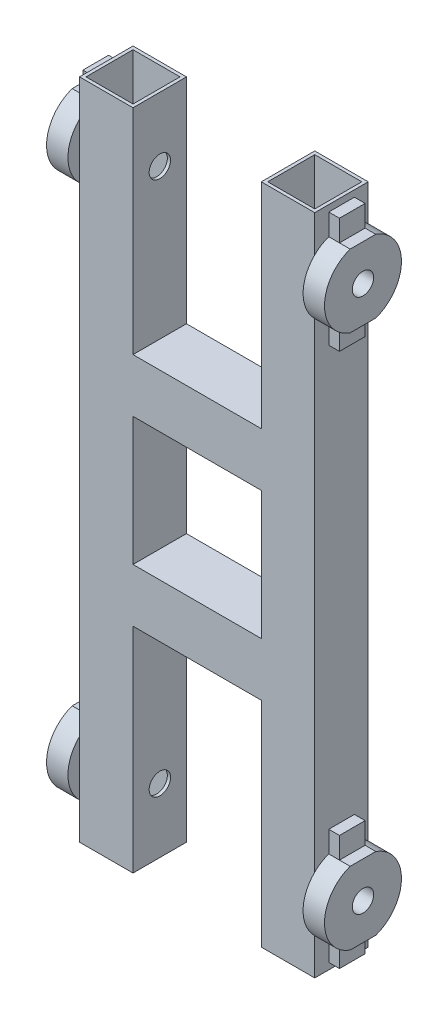
SolidWorks part; units mm, degrees
ref_plane "Front Plane" through (0, 0, 0) normal (0, 0, 1) x (1, 0, 0)
ref_plane "Top Plane" through (0, 0, 0) normal (0, 1, 0) x (1, 0, 0)
ref_plane "Right Plane" through (0, 0, 0) normal (1, 0, 0) x (0, 0, -1)
sketch "Sketch1" plane through (0, 0, 0) normal (0, 1, 0) x (1, 0, 0)
  line L0 (0, 63.6278) -> (0, -69.3975) construction
  line L1 (-105.4586, 0) -> (105.4586, 0) construction
  line L2 (19.5, 10.942) -> (19.5, -11.058)
  line L3 (18, 12.442) -> (43, 12.442)
  line L4 (18, 12.442) -> (18, -12.558)
  line L5 (18, -12.558) -> (43, -12.558)
  line L6 (43, 12.442) -> (43, -12.558)
  line L7 (19.5, -11.058) -> (41.5, -11.058)
  line L8 (41.5, 10.942) -> (41.5, -11.058)
  line L13 (19.5, 10.942) -> (41.5, 10.942)
  point P5 (30.442, 0)
  point P10 (30.5, -0.058)
  dimension "D1" = 25
  dimension "D2" = 25
  dimension "D3" = 18
  dimension "D4" = 1.5
extrude "Boss-Extrude1" add sketch "Sketch1" along normal blind 310
sketch "Sketch2" plane through (18, 0, 0) normal (-1, 0, 0) x (0, 0, 1)
  line L5 (12.558, 310) -> (12.558, 0) construction
  line L6 (-12.442, 210) -> (12.558, 210)
  line L7 (-12.442, 210) -> (-12.442, 185)
  line L8 (-12.442, 185) -> (12.558, 185)
  line L9 (12.558, 210) -> (12.558, 185)
  line L10 (-12.442, 210) -> (12.558, 185) construction
  line L11 (-12.442, 185) -> (12.558, 210) construction
  line L12 (-12.442, 310) -> (12.558, 310) construction
  line L13 (-10.942, 208.5) -> (-10.942, 186.5)
  line L14 (-12.442, 125) -> (12.558, 125)
  line L15 (-12.442, 125) -> (-12.442, 100)
  line L16 (-12.442, 100) -> (12.558, 100)
  line L17 (12.558, 125) -> (12.558, 100)
  line L18 (-12.442, 125) -> (12.558, 100) construction
  line L19 (-12.442, 100) -> (12.558, 125) construction
  line L20 (-10.942, 186.5) -> (11.058, 186.5)
  line L21 (11.058, 208.5) -> (11.058, 186.5)
  line L22 (-10.942, 208.5) -> (11.058, 208.5)
  line L23 (-10.942, 123.5) -> (-10.942, 101.5)
  line L24 (-10.942, 101.5) -> (11.058, 101.5)
  line L25 (11.058, 123.5) -> (11.058, 101.5)
  line L26 (-10.942, 123.5) -> (11.058, 123.5)
  point P0 (0.058, 197.5)
  point P9 (0.058, 112.5)
  dimension "D1" = 25
  dimension "D2" = 25
  dimension "D3" = 100
  dimension "D4" = 25
  dimension "D5" = 25
  dimension "D8" = 60
  dimension "D6" = 1.5
  dimension "D7" = 1.5
extrude "Boss-Extrude2" add sketch "Sketch2" along normal blind 30
sketch "Sketch8" plane through (18, 0, 0) normal (-1, 0, 0) x (0, 0, 1)
  line L0 (0, 340.3057) -> (0, -30.6599) construction
  line L1 (-12.442, 310) -> (12.558, 310) construction
  line L2 (-12.442, 0) -> (12.558, 0) construction
  circle A0 centre (0, 280) radius 5
  circle A1 centre (0, 30) radius 5
  point P11 (0, 0)
  dimension "D1" = 30
  dimension "D2" = 30
extrude "Cut-Extrude1" cut sketch "Sketch8" against normal blind 25
sketch "Sketch9" plane through (43, 0, 0) normal (1, 0, 0) x (0, 0, -1)
  line L0 (-6, 13.0294) -> (-6, 3.0294)
  line L24 (-6, 3.0294) -> (6, 3.0294)
  line L25 (6, 3.0294) -> (6, 13.0294)
  line L26 (-6, 46.9706) -> (-6, 56.9706)
  line L27 (-6, 56.9706) -> (6, 56.9706)
  line L28 (6, 56.9706) -> (6, 46.9706)
  circle A4 centre (0, 30) radius 5
  circle A5 centre (0, 30) radius 18
  arc A6 (-6, 46.9706) -> (6, 46.9706) centre (0, 30) cw
  arc A7 (-6, 13.0294) -> (6, 13.0294) centre (0, 30) ccw
  circle M17 centre (0, 30) radius 5
  line M21 (-12.558, 310) -> (-12.558, 0)
  dimension "D1" = 10
  dimension "D5" = 10
  dimension "D3" = 12
  dimension "D2" = 10
  dimension "D4" = 12
extrude "Boss-Extrude3" add sketch "Sketch9" along normal blind 10 contours A5 M17 | A5 L0 L24 L25 | A5 M21 | A5 L28 L27 L26 | A4
sketch "Sketch10" plane through (43, 0, 0) normal (1, 0, 0) x (0, 0, -1)
  line L0 (-6, 296.9706) -> (-6, 306.9706)
  line L1 (-6, 306.9706) -> (6, 306.9706)
  line L2 (6, 306.9706) -> (6, 296.9706)
  line L3 (-6, 263.0294) -> (-6, 253.0294)
  line L4 (-6, 253.0294) -> (6, 253.0294)
  line L5 (6, 253.0294) -> (6, 263.0294)
  circle A0 centre (0, 280) radius 18
  arc A1 (-6, 296.9706) -> (6, 296.9706) centre (0, 280) cw
  arc A2 (-6, 263.0294) -> (6, 263.0294) centre (0, 280) ccw
  circle A3 centre (0, 280) radius 5
  dimension "D1" = 12
  dimension "D2" = 10
  dimension "D3" = 10
  dimension "D4" = 10
  dimension "D5" = 12
  dimension "D6" = 10
extrude "Boss-Extrude4" add sketch "Sketch10" along normal blind 10
sketch "Sketch11" plane through (53, 0, 0) normal (1, 0, 0) x (0, 0, -1)
  line L0 (-6, 13.0294) -> (6, 13.0294)
  line L1 (6, 13.0294) -> (6, 3.0294)
  line L2 (-6, 3.0294) -> (6, 3.0294) construction
  line L3 (6, 3.0294) -> (6, 13.0294) construction
  line L4 (6, 3.0294) -> (-6, 3.0294)
  line L5 (-6, 3.0294) -> (-6, 13.0294)
  line L6 (-6, 46.9706) -> (6, 46.9706)
  line L7 (6, 46.9706) -> (6, 56.9706)
  line L8 (6, 56.9706) -> (-6, 56.9706)
  line L9 (-6, 56.9706) -> (-6, 46.9706)
  line L10 (-6, 263.0294) -> (-6, 253.0294)
  line L11 (-6, 253.0294) -> (6, 253.0294)
  line L12 (6, 253.0294) -> (6, 263.0294)
  line L13 (6, 263.0294) -> (-6, 263.0294)
  line L14 (-6, 296.9706) -> (-6, 306.9706)
  line L15 (-6, 306.9706) -> (6, 306.9706)
  line L16 (6, 306.9706) -> (6, 296.9706)
  line L17 (6, 296.9706) -> (-6, 296.9706)
  arc A0 (-6, 46.9706) -> (-6, 13.0294) centre (0, 30) ccw construction
extrude "Cut-Extrude2" cut sketch "Sketch11" against normal blind 5
mirror "Mirror1" about plane through (-12, 0, 0) normal (-1, 0, 0) of "Cut-Extrude2", "Boss-Extrude1", "Boss-Extrude2", "Cut-Extrude1", "Boss-Extrude3", "Boss-Extrude4"
